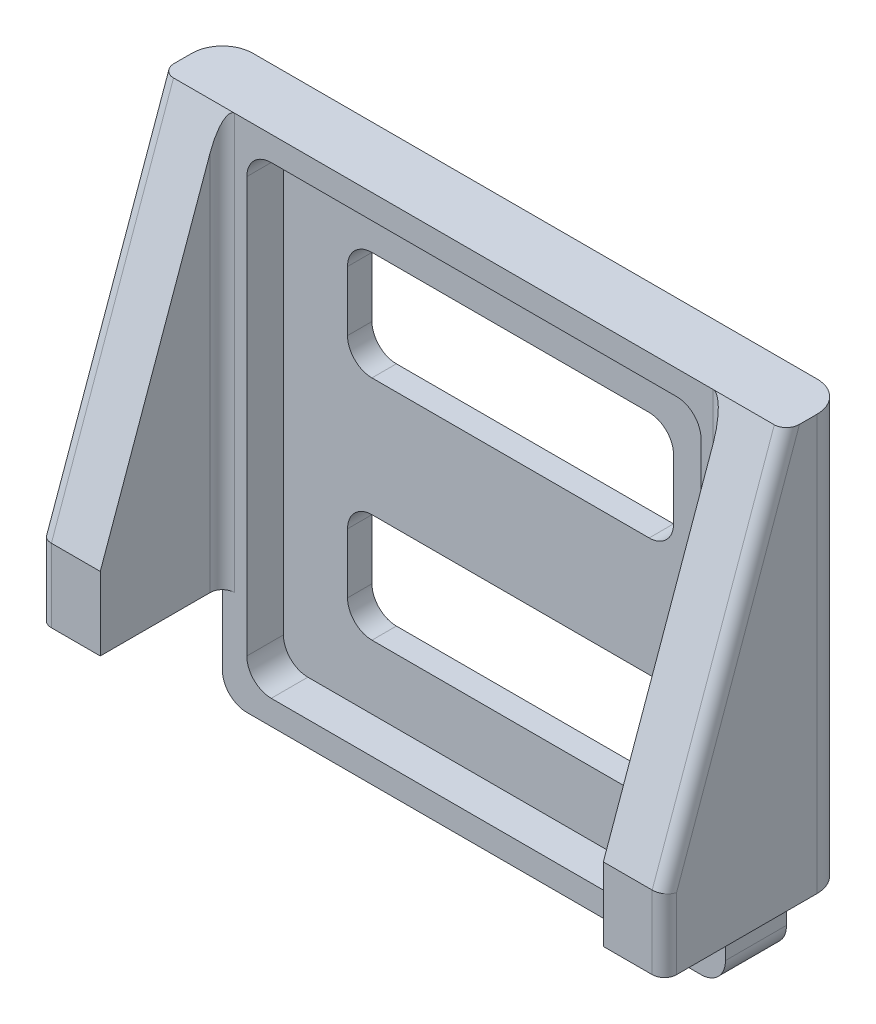
SolidWorks part; units mm, degrees
ref_plane "Front Plane" through (0, 0, 0) normal (0, 0, 1) x (1, 0, 0)
ref_plane "Top Plane" through (0, 0, 0) normal (0, 1, 0) x (1, 0, 0)
ref_plane "Right Plane" through (0, 0, 0) normal (1, 0, 0) x (0, 0, -1)
sketch "Sketch1" plane through (0, 0, 0) normal (0, 0, 1) x (1, 0, 0)
  line L1 (0, 0) -> (41.2, 0)
  line L2 (0, 0) -> (0, -42)
  line L3 (0, -42) -> (41.2, -42)
  line L4 (41.2, 0) -> (41.2, -42)
  dimension "D1" = 41.2
  dimension "D2" = 42
extrude "Boss-Extrude1" add sketch "Sketch1" along normal blind 5 contours L1 L4 L3 L2
sketch "Sketch2" plane through (0, 0, 5) normal (0, 0, 1) x (1, 0, 0)
  line L0 (0, 0) -> (41.2, 0) construction
  line L1 (4, -2) -> (37.2, -2)
  line L2 (2, -4) -> (2, -38)
  line L3 (4, -40) -> (37.2, -40)
  line L4 (39.2, -4) -> (39.2, -38)
  line L5 (0, -42) -> (41.2, -42) construction
  line L6 (0, 0) -> (0, -42) construction
  line L7 (41.2, 0) -> (41.2, -42) construction
  arc A0 (37.2, -2) -> (39.2, -4) centre (37.2, -4) cw
  arc A1 (37.2, -40) -> (39.2, -38) centre (37.2, -38) ccw
  arc A2 (2, -38) -> (4, -40) centre (4, -38) ccw
  arc A3 (4, -2) -> (2, -4) centre (4, -4) ccw
  dimension "D5" = 2
  dimension "D1" = 2
  dimension "D2" = 2
  dimension "D3" = 2
  dimension "D4" = 2
extrude "Cut-Extrude1" cut sketch "Sketch2" against normal blind 3
sketch "Sketch3" plane through (0, 0, 2) normal (0, 0, 1) x (1, 0, 0)
  line L0 (37.2, -2) -> (4, -2) construction
  line L1 (9.25, -7.25) -> (31.95, -7.25)
  line L2 (7.25, -9.25) -> (7.25, -14.15)
  line L3 (9.25, -16.15) -> (31.95, -16.15)
  line L4 (33.95, -9.25) -> (33.95, -14.15)
  line L5 (9.25, -25.85) -> (31.95, -25.85)
  line L6 (7.25, -27.85) -> (7.25, -32.75)
  line L7 (9.25, -34.75) -> (31.95, -34.75)
  line L8 (33.95, -27.85) -> (33.95, -32.75)
  line L9 (4, -40) -> (37.2, -40) construction
  line L10 (2, -4) -> (2, -38) construction
  line L11 (39.2, -38) -> (39.2, -4) construction
  arc A0 (31.95, -34.75) -> (33.95, -32.75) centre (31.95, -32.75) ccw
  arc A1 (7.25, -32.75) -> (9.25, -34.75) centre (9.25, -32.75) ccw
  arc A2 (9.25, -25.85) -> (7.25, -27.85) centre (9.25, -27.85) ccw
  arc A3 (31.95, -25.85) -> (33.95, -27.85) centre (31.95, -27.85) cw
  arc A4 (31.95, -7.25) -> (33.95, -9.25) centre (31.95, -9.25) cw
  arc A5 (31.95, -16.15) -> (33.95, -14.15) centre (31.95, -14.15) ccw
  arc A6 (7.25, -14.15) -> (9.25, -16.15) centre (9.25, -14.15) ccw
  arc A7 (9.25, -7.25) -> (7.25, -9.25) centre (9.25, -9.25) ccw
  dimension "D9" = 2
  dimension "D1" = 5.25
  dimension "D2" = 5.25
  dimension "D3" = 5.25
  dimension "D4" = 5.25
  dimension "D5" = 5.25
  dimension "D6" = 5.25
  dimension "D7" = 9.7
  dimension "D8" = 8.9
extrude "Cut-Extrude2" cut sketch "Sketch3" against normal up to surface (2 mm away) up to face at (20.6, -21, 0)
ref_plane "Plane1" through (0, -34, 0) normal (0, -1, 0) x (-1, 0, 0)
sketch "Sketch6" plane through (41.2, 0, 0) normal (1, 0, 0) x (0, 0, -1)
  line L0 (-5, 0) -> (-5, -42) construction
  line L1 (-5, -28) -> (0, -28)
  line L2 (-5, -28) -> (-5, -34)
  line L3 (-5, -34) -> (0, -34)
  line L4 (0, -28) -> (0, -34)
  line L5 (0, 0) -> (0, -42) construction
  line L6 (-12.2851, -34) -> (12.2851, -34) construction
  dimension "D1" = 6
sketch "Sketch7" plane through (0, 0, 0) normal (-1, 0, 0) x (0, 0, 1)
  line L0 (0, 0) -> (0, -42) construction
  line L1 (0, -28) -> (5, -28)
  line L2 (0, -28) -> (0, -34)
  line L3 (0, -34) -> (5, -34)
  line L4 (5, -28) -> (5, -34)
  line L5 (5, 0) -> (5, -42) construction
  line L6 (-12.2851, -34) -> (12.2851, -34) construction
  dimension "D1" = 6
sketch "Sketch8" plane through (0, 0, 0) normal (0, 0, -1) x (-1, 0, 0)
  line L0 (-33.95, -27.85) -> (-33.95, -32.75) construction
  line L1 (-41.2, -28) -> (-33.95, -28)
  line L2 (-41.2, -28) -> (-41.2, -34)
  line L3 (-41.2, -34) -> (-33.95, -34)
  line L4 (-33.95, -28) -> (-33.95, -34)
  line L5 (-12.2851, -34) -> (12.2851, -34) construction
sketch "Sketch9" plane through (0, 0, 0) normal (0, 0, -1) x (-1, 0, 0)
  line L0 (-7.25, -32.75) -> (-7.25, -27.85) construction
  line L1 (0, -28) -> (-7.25, -28)
  line L2 (0, -28) -> (0, -34)
  line L3 (0, -34) -> (-7.25, -34)
  line L4 (-7.25, -28) -> (-7.25, -34)
  line L5 (-12.2851, -34) -> (12.2851, -34) construction
extrude "Boss-Extrude2" add sketch "Sketch6" along normal blind 5
extrude "Boss-Extrude3" add sketch "Sketch7" along normal blind 5
extrude "Boss-Extrude4" [suppressed] add sketch "Sketch8" along normal blind 6
extrude "Boss-Extrude5" [suppressed] add sketch "Sketch9" along normal blind 6
sketch "Sketch13" plane through (0, 0, 5) normal (0, 0, 1) x (1, 0, 0)
  line L1 (46.2, -34) -> (41.2, -34)
  line L2 (46.2, -34) -> (46.2, -28)
  line L3 (46.2, -28) -> (41.2, -28)
  line L4 (41.2, -34) -> (41.2, -28)
  line L5 (0, -34) -> (-5, -34)
  line L6 (0, -34) -> (0, -28)
  line L7 (0, -28) -> (-5, -28)
  line L8 (-5, -34) -> (-5, -28)
extrude "Boss-Extrude6" add sketch "Sketch13" along normal blind 10
ref_plane "Plane2" through (20.6, 0, 0) normal (1, 0, 0) x (0, 0, -1)
sketch "Sketch10" plane through (0, -28, 0) normal (0, 1, 0) x (1, 0, 0)
  line L0 (41.2, -7.5) -> (46.2, -7.5) construction
  line L3 (43.7, -15) -> (43.7, 0) construction
  line L5 (46.2, 0) -> (41.2, 0) construction
  line L6 (46.2, -15) -> (41.2, -15) construction
  line L7 (46.2, 0) -> (46.2, -15) construction
  line L8 (41.2, 0) -> (41.2, -5) construction
  circle A0 centre (43.7, -3) radius 1.5
  circle A1 centre (43.7, -12) radius 1.5
  point P16 (46.2, -7.5)
  dimension "D1" = 3
  dimension "D2" = 4.5
extrude "Cut-Extrude3" cut sketch "Sketch10" against normal blind 6
mirror "Mirror1" about plane through (20.6, 0, 0) normal (1, 0, 0) of "Cut-Extrude3"
sketch "Sketch12" [suppressed] plane through (0, -28, 0) normal (0, 1, 0) x (1, 0, 0)
  line L0 (37.575, 0) -> (37.575, 6) construction
  line L1 (33.95, 0) -> (41.2, 0) construction
  line L2 (33.95, 6) -> (41.2, 6) construction
  line L3 (41.2, 3) -> (33.95, 3) construction
  line L4 (41.2, 6) -> (41.2, 0) construction
  line L5 (33.95, 6) -> (33.95, 0) construction
  circle A0 centre (37.575, 3) radius 1.5
  dimension "D1" = 3
extrude "Cut-Extrude4" [suppressed] cut sketch "Sketch12" against normal blind 6
mirror "Mirror2" [suppressed] about plane through (20.6, 0, 0) normal (1, 0, 0)
fillet "Fillet3" [suppressed] radius 2
fillet "Fillet4" radius 2.5 2 edges at (46.2, -31, 0) (-5, -31, 0)
sketch "Sketch14" [suppressed] plane through (0, -28, 0) normal (0, 1, 0) x (1, 0, 0)
  line L0 (41.2, 3.5) -> (38.7, 6)
  line L3 (41.2, 6) -> (41.2, 0) construction
  line L6 (35.95, 6) -> (41.2, 6) construction
  dimension "D1" = 2.5
  dimension "D2" = 2.5
extrude "Cut-Extrude6" [suppressed] cut sketch "Sketch14" against normal blind 6 and the other way through all flip side to cut
sketch "Sketch15" [suppressed] plane through (0, -28, 0) normal (0, 1, 0) x (1, 0, 0)
  line L0 (2.5, 6) -> (0, 3.5)
  line L3 (0, 6) -> (0, 0) construction
  line L4 (0, 6) -> (7.25, 6) construction
  dimension "D1" = 2.5
  dimension "D2" = 2.5
extrude "Cut-Extrude7" [suppressed] cut sketch "Sketch15" against normal blind 6 and the other way through all flip side to cut
sketch "Sketch16" plane through (0, -28, 0) normal (0, 1, 0) x (1, 0, 0)
  line L0 (41.2, 0) -> (43.7, 0)
  line L1 (41.2, -5) -> (46.2, -5)
  line L2 (46.2, -2.5) -> (46.2, -15) construction
  line L3 (46.2, -5) -> (46.2, -2.5)
  line L5 (41.2, 0) -> (41.2, -5)
  arc A0 (46.2, -2.5) -> (43.7, 0) centre (43.7, -2.5) ccw
extrude "Boss-Extrude7" add sketch "Sketch16" along normal up to surface (28 mm away) up to face at (20.6, 0, 2.5)
ref_plane "Plane3" through (43.7, 0, 0) normal (1, 0, 0) x (0, 0, -1)
ref_plane "Plane4" through (20.6, 0, 0) normal (1, 0, 0) x (0, 0, -1)
sketch "Sketch17" plane through (46.2, 0, 0) normal (1, 0, 0) x (0, 0, -1)
  line L0 (-5, 0) -> (-15, -28)
  line L1 (-15, -28) -> (-5, -28)
  line L2 (-5, 0) -> (-5, -28) construction
  line L3 (-5, -28) -> (-15, -28) construction
  line L4 (-5, -28) -> (-5, 0)
extrude "Boss-Extrude8" add sketch "Sketch17" against normal blind 5
fillet "Fillet10" radius 1 2 edges at (46.2, -31, 15) (46.2, -14, 10)
mirror "Mirror3" about plane through (20.6, 0, 0) normal (1, 0, 0) of "Boss-Extrude7", "Boss-Extrude8"
fillet "Fillet12" radius 2 2 edges at (41.2, -42, 2.5) (0, -42, 2.5)
fillet "Fillet13" radius 1 2 edges at (-5, -31, 15) (-5, -14, 10)
fillet "Fillet14" radius 1 2 edges at (41.2, -17, 5) (0, -17, 5)
